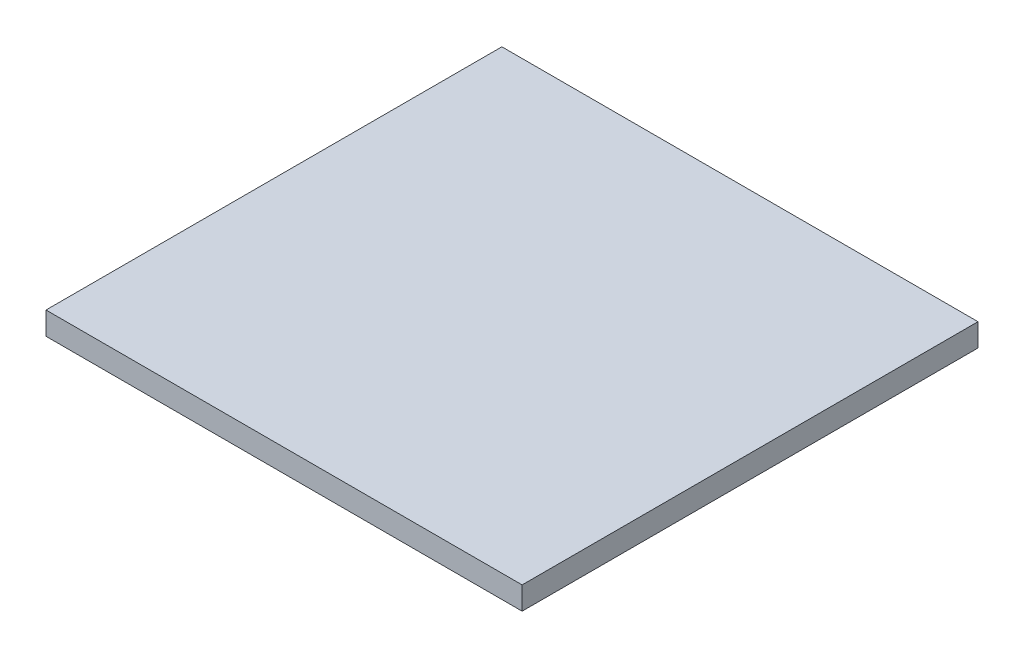
SolidWorks part; units mm, degrees
ref_plane "Alzado" through (0, 0, 0) normal (0, 0, 1) x (1, 0, 0)
ref_plane "Planta" through (0, 0, 0) normal (0, 1, 0) x (1, 0, 0)
ref_plane "Vista lateral" through (0, 0, 0) normal (1, 0, 0) x (0, 0, -1)
sketch "Croquis1" plane through (0, 0, 0) normal (0, 1, 0) x (1, 0, 0)
  line L1 (-188, 180) -> (188, 180)
  line L2 (-188, 180) -> (-188, -180)
  line L3 (-188, -180) -> (188, -180)
  line L4 (188, 180) -> (188, -180)
  line L5 (-188, 180) -> (188, -180) construction
  line L6 (-188, -180) -> (188, 180) construction
  point P0 (0, 0)
  dimension "D1" = 376
  dimension "D2" = 360
extrude "Saliente-Extruir1" add sketch "Croquis1" along normal blind 18
